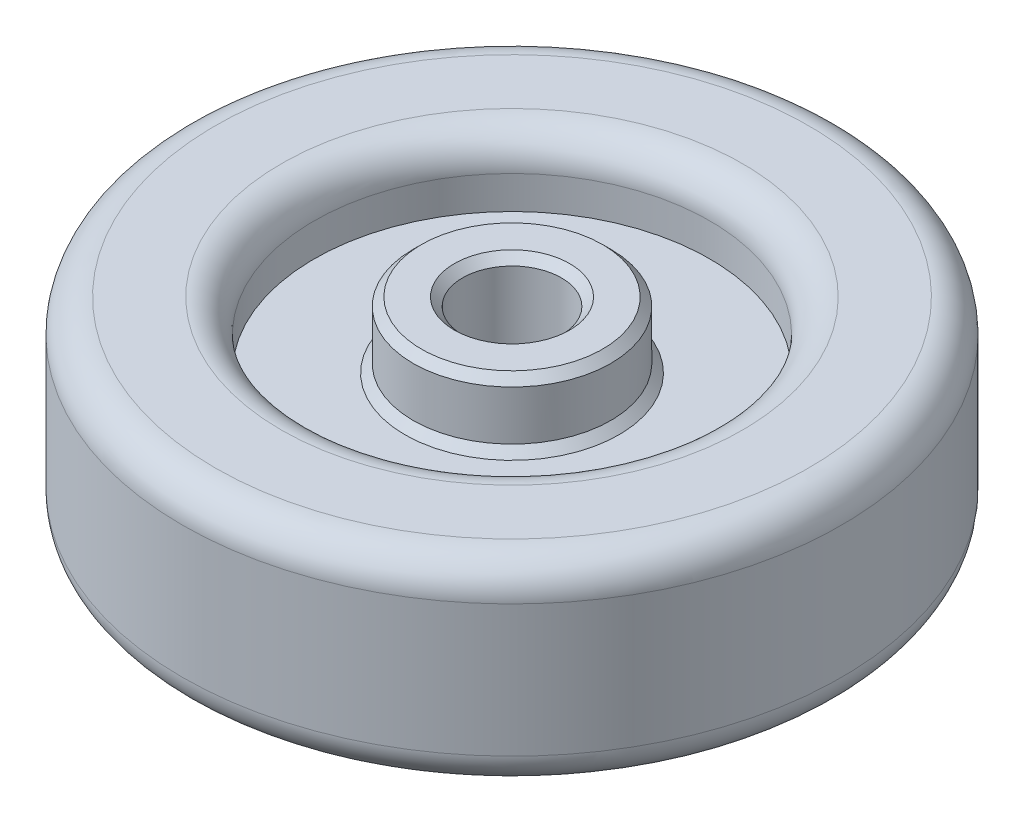
SolidWorks part; units mm, degrees
ref_plane "Front Plane" through (0, 0, 0) normal (0, 0, 1) x (1, 0, 0)
ref_plane "Top Plane" through (0, 0, 0) normal (0, 1, 0) x (1, 0, 0)
ref_plane "Right Plane" through (0, 0, 0) normal (1, 0, 0) x (0, 0, -1)
sketch "Sketch1" plane through (0, 0, 0) normal (0, 1, 0) x (1, 0, 0)
  circle A0 centre (0, 0) radius 15.875
  dimension "D1" = 31.75
extrude "Boss-Extrude1" add sketch "Sketch1" along normal blind 9.525
sketch "Sketch2" plane through (0, 9.525, 0) normal (0, 1, 0) x (1, 0, 0)
  circle A0 centre (0, 0) radius 9.525
  circle A1 centre (0, 0) radius 4.7625
  dimension "D1" = 19.05
  dimension "D2" = 9.525
extrude "Cut-Extrude1" cut sketch "Sketch2" against normal blind 3.175
sketch "Sketch3" plane through (0, 9.525, 0) normal (0, 1, 0) x (1, 0, 0)
  circle A0 centre (0, 0) radius 2.3813
  dimension "D1" = 4.7625
extrude "Cut-Extrude2" cut sketch "Sketch3" against normal through all both and the other way through all
fillet "Fillet2" radius 1.5875 3 edges at (0, 0, 15.875) (0, 9.525, 15.875) (0, 9.525, 9.525)
chamfer "Chamfer2" distance 0.3969 angle 45 4 edges at (0, 0, 2.3813) (0, 9.525, 2.3813) (0, 9.525, 4.7625) (0, 6.35, 4.7625)
